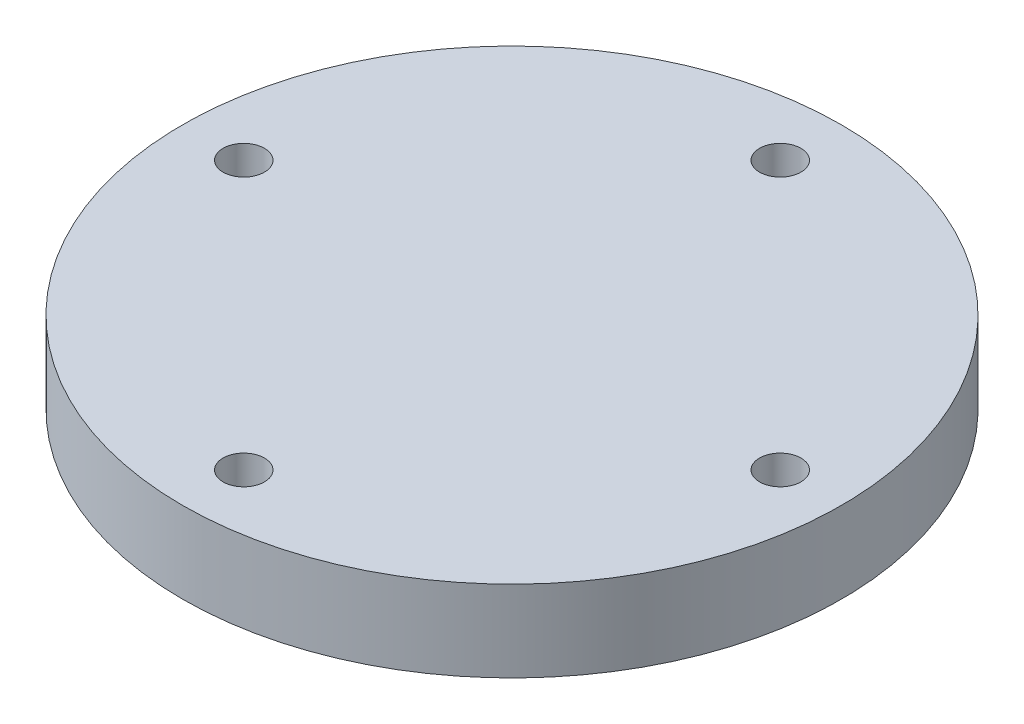
SolidWorks part; units mm, degrees
ref_plane "前视基准面" through (0, 0, 0) normal (0, 0, 1) x (1, 0, 0)
ref_plane "上视基准面" through (0, 0, 0) normal (0, 1, 0) x (1, 0, 0)
ref_plane "右视基准面" through (0, 0, 0) normal (1, 0, 0) x (0, 0, -1)
sketch "草图1" plane through (0, 0, 0) normal (0, 1, 0) x (1, 0, 0)
  circle A0 centre (0, 0) radius 21.5
  dimension "D1" = 43
extrude "凸台-拉伸1" add sketch "草图1" along normal blind 5.3
sketch "草图2" plane through (0, 5.3, 0) normal (0, 1, 0) x (1, 0, 0)
  line L0 (0, 0) -> (-17.5, 0) construction
  circle A0 centre (-17.5, 0) radius 1.35
  circle A1 centre (0, 17.5) radius 1.35
  circle A2 centre (17.5, 0) radius 1.35
  circle A3 centre (0, -17.5) radius 1.35
  point P4 (-9.4833, -12.9047)
  point P5 (0, 0)
  point P13 (0, 0)
  dimension "D2" = 2.7
  dimension "D1" = 17.5
  dimension "D3" = 4
extrude "切除-拉伸1" cut sketch "草图2" against normal up to next
